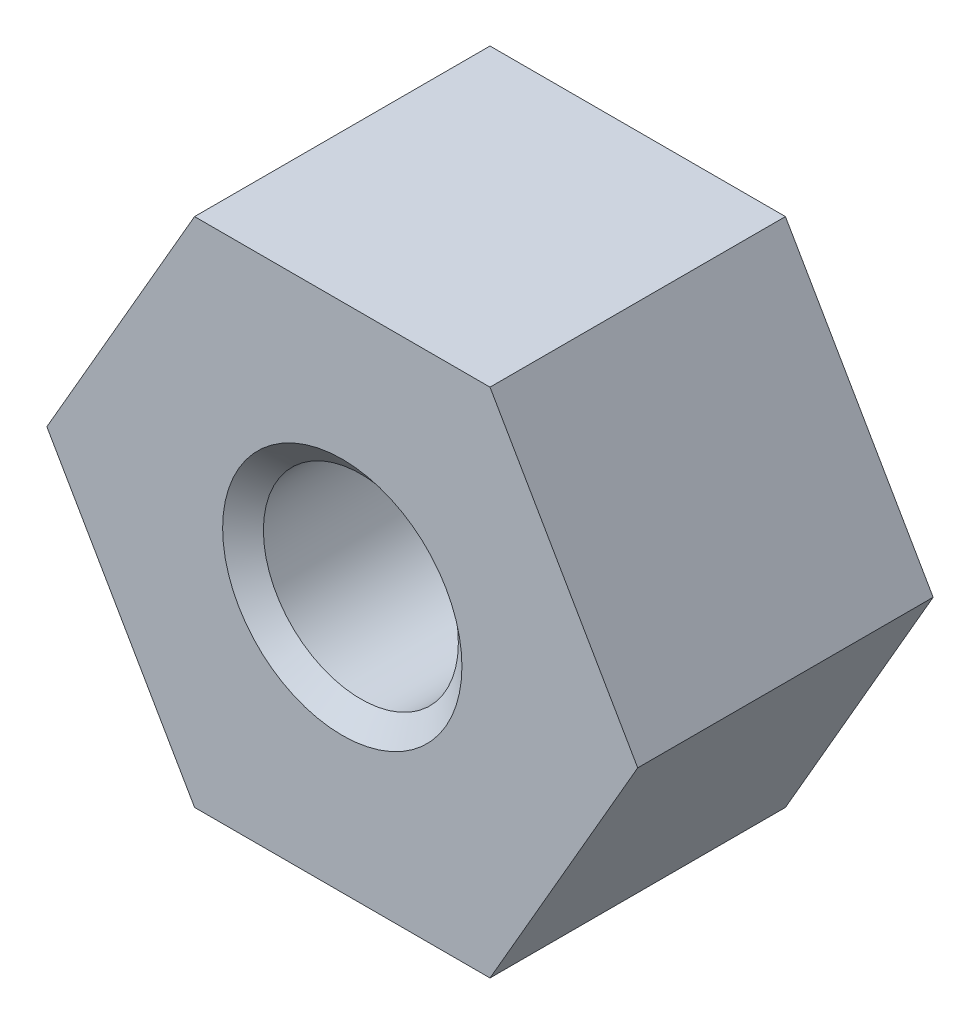
SolidWorks part; units mm, degrees
ref_plane "Front Plane" through (0, 0, 0) normal (0, 0, 1) x (1, 0, 0)
ref_plane "Top Plane" through (0, 0, 0) normal (0, 1, 0) x (1, 0, 0)
ref_plane "Right Plane" through (0, 0, 0) normal (1, 0, 0) x (0, 0, -1)
sketch "Sketch1" plane through (0, 0, 0) normal (0, 0, 1) x (1, 0, 0)
  line L1 (5, 0) -> (2.5, 4.3301)
  line L2 (2.5, 4.3301) -> (-2.5, 4.3301)
  line L3 (-2.5, 4.3301) -> (-5, 0)
  line L4 (-5, 0) -> (-2.5, -4.3301)
  line L5 (-2.5, -4.3301) -> (2.5, -4.3301)
  line L6 (2.5, -4.3301) -> (5, 0)
  circle A0 centre (0, 0) radius 4.3301 construction
  dimension "D1" = 10
extrude "Boss-Extrude1" add sketch "Sketch1" along normal mid plane 5
hole_wizard "M4x0.7 Tapped Hole1" positions "Sketch2" profile "Sketch3" tap size "M4x0.7" standard "ANSI Metric" end condition up to next
sketch "Sketch2" plane through (0, 0, 2.5) normal (0, 0, 1) x (1, 0, 0)
  point P0 (0, 0)
sketch "Sketch3" plane through (0, 0, 2.5) normal (1, 0, 0) x (0, -1, 0)
  line L0 (0, 0) -> (0, 5)
  line L1 (0, 5) -> (1.65, 5)
  line L2 (1.65, 5) -> (1.65, 0.3147)
  line L3 (1.65, 0.3147) -> (2.025, 0)
  line L5 (2.025, 0) -> (0, 0)
  line L6 (-1.65, 0.3147) -> (-2.025, 0) construction
  line L11 (0, -6.35) -> (0, 107.95) construction
  dimension "Thru Tap Drill Dia." = 3.3
  dimension "Thru Tap Drill Depth" = 5
  dimension "Near C'Sink Dia." = 4.05
  dimension "Near C'Sink Angle" = 100
cosmetic thread "Hole Thread1" parameters "D2"=4
sketch "Sketch6" plane through (0, 0, 0) normal (1, 0, 0) x (0, 0, -1)
  line L0 (-2.5, 3.3301) -> (-1.5, 4.3301)
  line L1 (-3.8307, 0) -> (4.7375, 0) construction
  line L3 (-1.5, 4.3301) -> (-2.5, 4.3301)
  line L4 (-2.5, 4.3301) -> (-2.5, 3.3301)
  dimension "D1" = 1
  dimension "D2" = 1
revolve "Cut-Revolve7" [suppressed] cut sketch "Sketch6" angle 360 about L3
